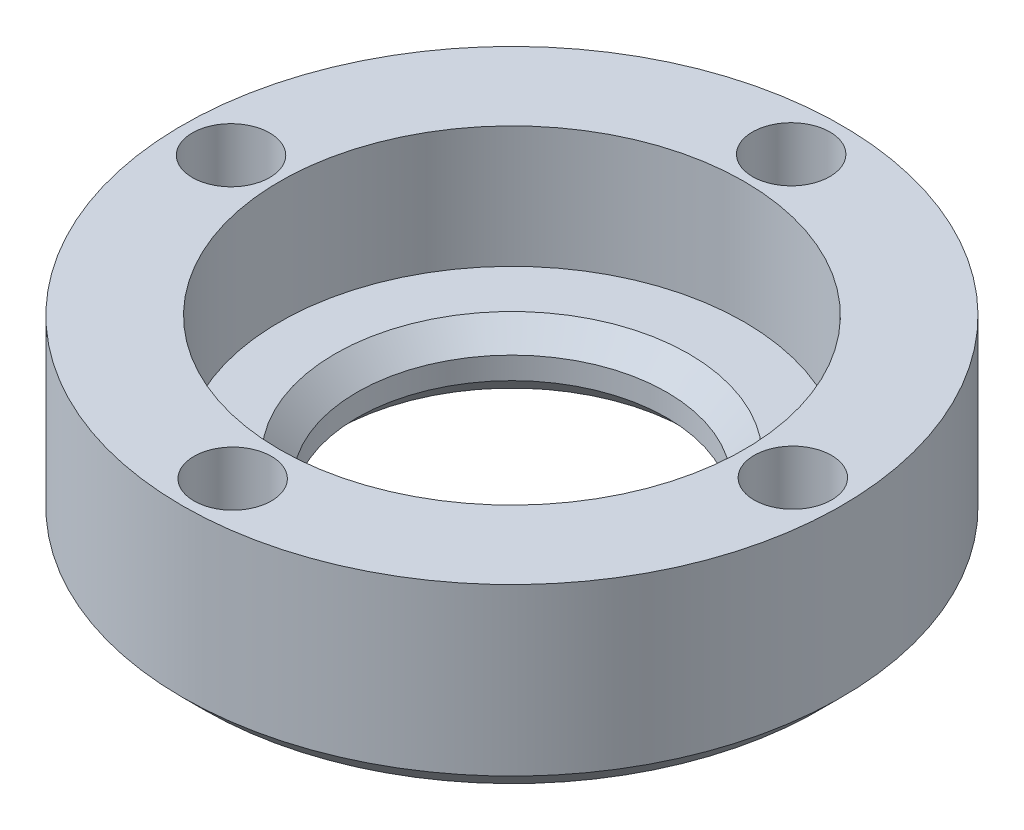
SolidWorks part; units mm, degrees
ref_plane "Front Plane" through (0, 0, 0) normal (1, 0, 0) x (0, 1, 0)
ref_plane "Top Plane" through (0, 0, 0) normal (0, 0, 1) x (0, 1, 0)
ref_plane "Right Plane" through (0, 0, 0) normal (0, 1, 0) x (-1, 0, 0)
sketch "Sketch1" plane through (0, 0, 0) normal (0, 1, 0) x (-1, 0, 0)
  circle A0 centre (0, 0) radius 14.9
  dimension "D1" = 29.8
extrude "Boss-Extrude1" add sketch "Sketch1" along normal blind 3
sketch "Sketch2" plane through (0, 3, 0) normal (0, 1, 0) x (-1, 0, 0)
  circle A0 centre (0, 0) radius 7
  dimension "D1" = 14
extrude "Cut-Extrude1" cut sketch "Sketch2" against normal through all
sketch "Sketch3" plane through (0, 3, 0) normal (0, 1, 0) x (-1, 0, 0)
  circle A0 centre (0, 0) radius 10.5
  circle A1 centre (0, 0) radius 14.9
  circle A2 centre (0, 0) radius 14.9 construction
  dimension "D1" = 21
extrude "Boss-Extrude2" add sketch "Sketch3" along normal blind 3.5
chamfer "Chamfer1" distance 1 angle 45 3 edges at (0, 3, 7) (0, 0, 14.9) (0, 0, 7)
sketch "Sketch4" plane through (0, 6.5, 0) normal (0, 1, 0) x (-1, 0, 0)
  line L0 (-10.5, 0) -> (-14.9, 0) construction
  circle A0 centre (0, 0) radius 10.5 construction
  circle A1 centre (0, 0) radius 10.5 construction
  circle A2 centre (0, 0) radius 14.9 construction
  circle A3 centre (-12.7, 0) radius 1.75
  arc A7 (-12.7, 0) -> (-12.5794, -1.7458) centre (0, 0) ccw construction
  arc A8 (-12.5794, -1.7458) -> (-12.5794, 1.7458) centre (0, 0) ccw construction
  circle A9 centre (-0.075, 12.7) radius 1.75
  circle A10 centre (12.625, 0.075) radius 1.75
  circle A11 centre (0, -12.625) radius 1.75
  arc A12 (-12.5794, 1.7458) -> (-12.7, 0) centre (0, 0) ccw construction
  point P20 (-0.125, 0.125)
  point P24 (-0.0375, 0.0375)
  dimension "D1" = 3.5
  dimension "D2" = 4
extrude "Cut-Extrude2" cut sketch "Sketch4" against normal blind 4
sketch "Sketch5" plane through (0, 6.5, 0) normal (0, 1, 0) x (-1, 0, 0)
  circle A1 centre (0, 0) radius 10.5 construction
  circle A16 centre (0, 0) radius 14.9
  circle A23 centre (0, 0) radius 14.9
  circle A24 centre (0, 0) radius 10.5
  circle A25 centre (0, -12.625) radius 1.75 construction
  circle A26 centre (12.625, 0.075) radius 1.75 construction
  circle A27 centre (-0.075, 12.7) radius 1.75 construction
  circle A28 centre (-12.7, 0) radius 1.75 construction
  circle A29 centre (0, -12.625) radius 1.75
  circle A30 centre (12.625, 0.075) radius 1.75
  circle A31 centre (-0.075, 12.7) radius 1.75
  circle A32 centre (-12.7, 0) radius 1.75
  dimension "D1" = 0
extrude "Boss-Extrude3" add sketch "Sketch5" along normal blind 2
